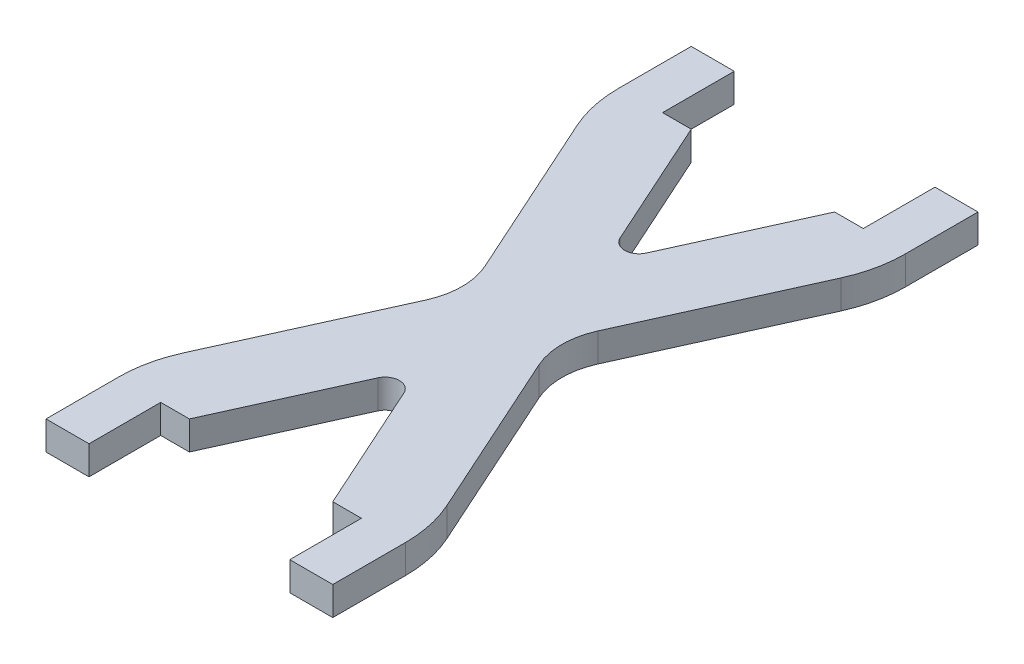
SolidWorks part; units mm, degrees
ref_plane "Front Plane" through (0, 0, 0) normal (0, 0, 1) x (1, 0, 0)
ref_plane "Top Plane" through (0, 0, 0) normal (0, 1, 0) x (1, 0, 0)
ref_plane "Right Plane" through (0, 0, 0) normal (1, 0, 0) x (0, 0, -1)
sketch "Sketch1" plane through (0, 0, 0) normal (0, 1, 0) x (1, 0, 0)
  line L0 (10, 0) -> (10, 35) construction
  line L1 (3, 0) -> (5, 0)
  line L2 (0, 0) -> (0, 2)
  line L3 (3, 35) -> (5, 35)
  line L4 (20, 0) -> (20, 2)
  line L6 (0, 35) -> (0, 40)
  line L7 (0, 40) -> (3, 40)
  line L8 (3, 35) -> (3, 40)
  line L9 (0, 17.5) -> (20, 17.5) construction
  line L10 (0, -5) -> (3, -5)
  line L11 (3, 0) -> (3, -5)
  line L12 (0, 0) -> (0, -5)
  line L13 (17, 35) -> (17, 40)
  line L14 (20, 40) -> (17, 40)
  line L15 (20, 35) -> (20, 40)
  line L16 (20, 0) -> (20, -5)
  line L17 (17, 0) -> (17, -5)
  line L18 (20, -5) -> (17, -5)
  line L19 (0, 33) -> (7, 17.5)
  line L20 (0, 2) -> (7, 17.5)
  line L21 (20, 33) -> (13, 17.5)
  line L22 (20, 2) -> (13, 17.5)
  line L23 (5, 35) -> (10, 23.9286)
  line L24 (15, 35) -> (10, 23.9286)
  line L25 (15, 0) -> (10, 11.0714)
  line L26 (5, 0) -> (10, 11.0714)
  line L27 (0, 33) -> (0, 35)
  line L28 (20, 33) -> (20, 35)
  line L29 (15, 35) -> (17, 35)
  line L30 (15, 0) -> (17, 0)
  dimension "D1" = 20
  dimension "D2" = 35
  dimension "D3" = 3
  dimension "D4" = 5
  dimension "D5" = 2
  dimension "D6" = 3
  dimension "D7" = 2
extrude "Boss-Extrude1" add sketch "Sketch1" along normal blind 2
fillet "Fillet1" radius 1 2 edges at (10, 1, -11.0714) (10, 1, -23.9286)
fillet "Fillet2" radius 5 2 edges at (7, 1, -17.5) (13, 1, -17.5)
fillet "Fillet3" radius 9 4 edges at (0, 1, -2) (0, 1, -33) (20, 1, -33) (20, 1, -2)
